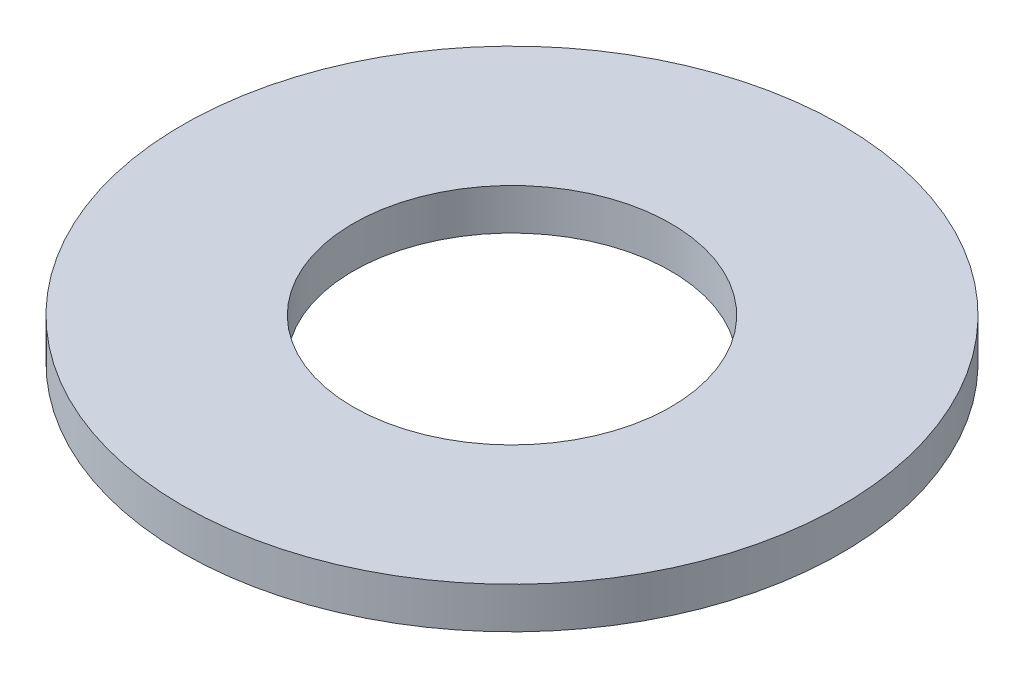
SolidWorks part; units mm, degrees
ref_plane "Front Plane" through (0, 0, 0) normal (0, 0, 1) x (1, 0, 0)
ref_plane "Top Plane" through (0, 0, 0) normal (0, 1, 0) x (1, 0, 0)
ref_plane "Right Plane" through (0, 0, 0) normal (1, 0, 0) x (0, 0, -1)
sketch "Sketch1" plane through (0, 0, 0) normal (0, 1, 0) x (1, 0, 0)
  circle A0 centre (0, 0) radius 5.6
  circle A1 centre (0, 0) radius 2.7
  dimension "D1" = 11.2
  dimension "D2" = 5.4
extrude "Boss-Extrude1" add sketch "Sketch1" along normal blind 0.7
